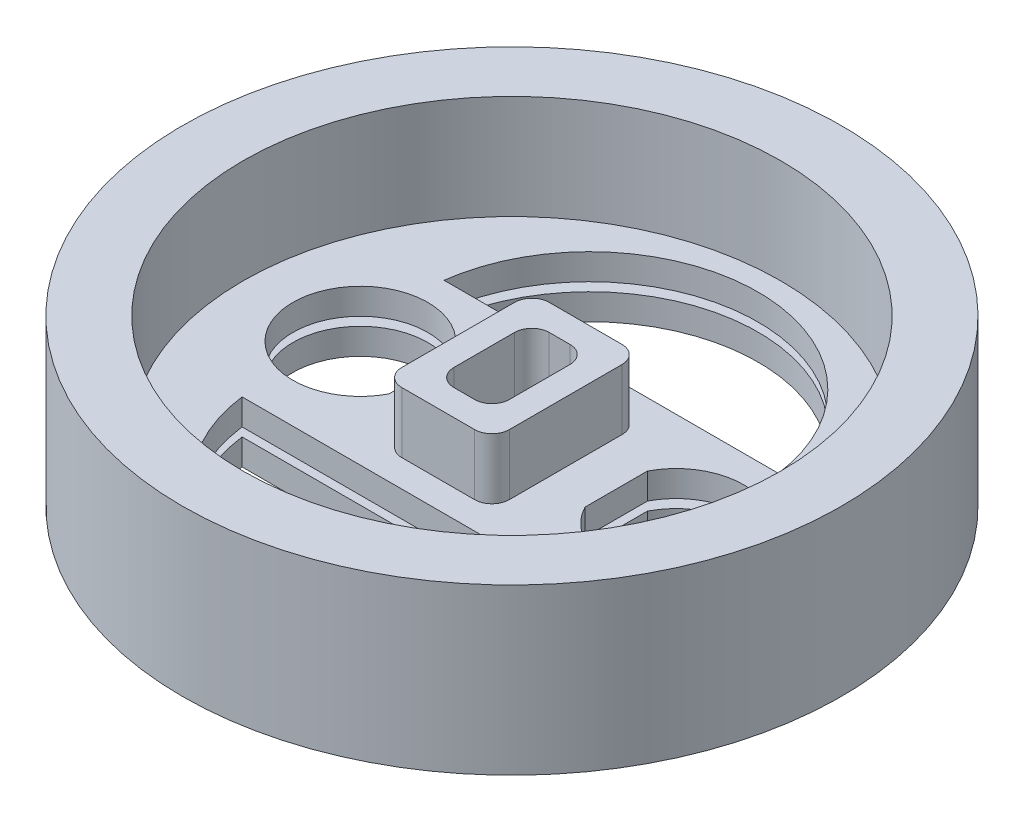
SolidWorks part; units mm, degrees
ref_plane "Front Plane" through (0, 0, 0) normal (0, 0, 1) x (1, 0, 0)
ref_plane "Top Plane" through (0, 0, 0) normal (0, 1, 0) x (1, 0, 0)
ref_plane "Right Plane" through (0, 0, 0) normal (1, 0, 0) x (0, 0, -1)
sketch "Sketch4" plane through (0, 0, 0) normal (0, 1, 0) x (1, 0, 0)
  line L0 (0, -46.7905) -> (24.3942, -46.7905) construction
  line L1 (0, -46.7905) -> (0, -24.9936) construction
  circle A0 centre (0, -46.7905) radius 17
  dimension "D1" = 34
extrude "Boss-Extrude3" add sketch "Sketch4" along normal blind 6 separate body
shell "Shell4" thickness 0.5
ref_plane "Plane2" through (0, 0, 0) normal (0, 1, 0) x (1, 0, 0)
sketch "Sketch5" plane through (0, 0, 0) normal (0, 1, 0) x (1, 0, 0)
  line L0 (17, -46.7905) -> (-25.0436, -46.7905) construction
  line L1 (1.6, -44.0405) -> (-1.6, -44.0405)
  line L2 (1.6, -44.0405) -> (1.6, -49.5405)
  line L3 (1.6, -49.5405) -> (-1.6, -49.5405)
  line L4 (-1.6, -44.0405) -> (-1.6, -49.5405)
  line L5 (0, -29.7905) -> (0, -85.3723) construction
  circle A0 centre (0, -46.7905) radius 17 construction
  circle A1 centre (0, -46.7905) radius 17 construction
  dimension "D1" = 5.5
  dimension "D2" = 3.2
  dimension "D3" = 2.75
  dimension "D4" = 1.6
extrude "Boss-Extrude4" add sketch "Sketch5" along normal blind 5
shell "Shell5" thickness 1.5
sketch "Sketch8" plane through (0, 1.5, 0) normal (0, 1, 0) x (1, 0, 0)
  line L0 (-9.7364, -40.9694) -> (9.5358, -40.9694)
  line L1 (3.1, -46.7905) -> (31.3222, -46.7905) construction
  line L2 (3.1, -51.0405) -> (3.1, -42.5405) construction
  line L3 (-9.7364, -52.6115) -> (9.5358, -52.6115)
  line L4 (-5.6513, -44.6283) -> (-5.6513, -48.2299)
  line L5 (0, -42.5405) -> (0, -27.4386) construction
  line L6 (3.1, -42.5405) -> (-3.1, -42.5405) construction
  line L7 (5.6513, -44.6283) -> (5.6513, -48.2299)
  arc A0 (-9.7364, -40.9694) -> (9.5358, -40.9694) centre (-0.1003, -42.217) cw
  arc A1 (-9.7364, -52.6115) -> (9.5358, -52.6115) centre (-0.1003, -51.3639) ccw
  arc A2 (-5.6513, -44.6283) -> (-5.6513, -48.2299) centre (-9.1002, -46.4291) ccw
  arc A3 (5.6513, -44.6283) -> (5.6513, -48.2299) centre (9.1002, -46.4291) cw
extrude "Cut-Extrude2" cut sketch "Sketch8" against normal through all
fillet "Fillet1" radius 1 8 edges at (-1.6, 2.5, 49.5405) (1.6, 2.5, 49.5405) (-1.6, 2.5, 44.0405) (1.6, 2.5, 44.0405) (-3.1, 3.25, 42.5405) (3.1, 3.25, 42.5405) (3.1, 3.25, 51.0405) (-3.1, 3.25, 51.0405)
